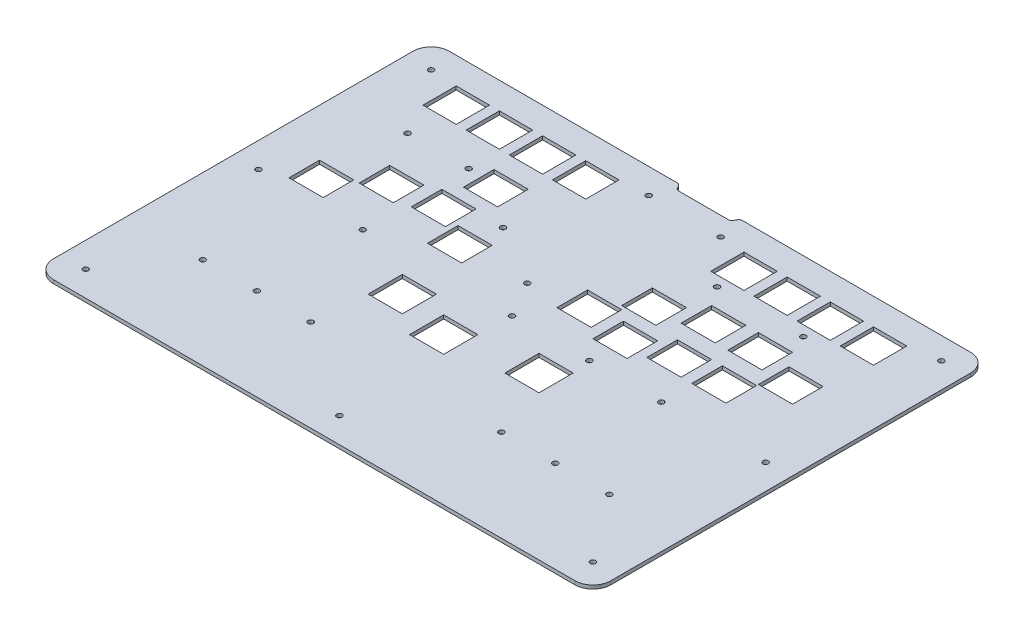
SolidWorks part; units mm, degrees
ref_plane "前视基准面" through (0, 0, 0) normal (0, 0, 1) x (1, 0, 0)
ref_plane "上视基准面" through (0, 0, 0) normal (0, 1, 0) x (1, 0, 0)
ref_plane "右视基准面" through (0, 0, 0) normal (1, 0, 0) x (0, 0, -1)
sketch "草图1" plane through (0, 0, 0) normal (0, 1, 0) x (1, 0, 0)
  line L0 (183.25, -128.5) -> (183.25, -131.5) construction
  line L1 (10, 0) -> (136.8844, 0)
  line L2 (0, -10) -> (0, -210)
  line L3 (10, -220) -> (300, -220)
  line L4 (310, -10) -> (310, -210)
  line L5 (28.75, -14.75) -> (47.25, -14.75)
  line L6 (28.75, -14.75) -> (28.75, -33.25)
  line L7 (28.75, -33.25) -> (47.25, -33.25)
  line L8 (173, -85) -> (173, 0) construction
  line L9 (173, -85) -> (310, -85) construction
  line L10 (190, -66) -> (190, 0) construction
  line L11 (215, -58) -> (215, 0) construction
  line L12 (241, -58) -> (241, 0) construction
  line L13 (247, -84) -> (247, 0) construction
  line L14 (222, -84) -> (222, 0) construction
  line L15 (0, -220) -> (310, 0) construction
  line L16 (241, -58) -> (310, -58) construction
  line L17 (247, -84) -> (310, -84) construction
  line L18 (215, -58) -> (310, -58) construction
  line L19 (222, -84) -> (310, -84) construction
  line L20 (190, -66) -> (310, -66) construction
  line L21 (310, -220) -> (0, 0) construction
  line L22 (141.1791, -3.5) -> (143.5, -3.5)
  line L23 (139.4291, -2.4682) -> (138.6344, -1.0318)
  line L24 (170.5709, -2.4682) -> (171.3656, -1.0318)
  line L25 (173.1156, 0) -> (300, 0)
  line L26 (155, -110) -> (155, -220) construction
  line L27 (47.25, -14.75) -> (47.25, -33.25)
  line L28 (28.75, -14.75) -> (47.25, -33.25) construction
  line L29 (28.75, -33.25) -> (47.25, -14.75) construction
  line L30 (52.75, -14.75) -> (71.25, -14.75)
  line L31 (52.75, -14.75) -> (52.75, -33.25)
  line L32 (52.75, -33.25) -> (71.25, -33.25)
  line L33 (71.25, -14.75) -> (71.25, -33.25)
  line L34 (52.75, -14.75) -> (71.25, -33.25) construction
  line L35 (52.75, -33.25) -> (71.25, -14.75) construction
  line L36 (76.75, -14.75) -> (95.25, -14.75)
  line L37 (76.75, -14.75) -> (76.75, -33.25)
  line L38 (76.75, -33.25) -> (95.25, -33.25)
  line L39 (95.25, -14.75) -> (95.25, -33.25)
  line L40 (76.75, -14.75) -> (95.25, -33.25) construction
  line L41 (76.75, -33.25) -> (95.25, -14.75) construction
  line L42 (100.75, -14.75) -> (119.25, -14.75)
  line L43 (100.75, -14.75) -> (100.75, -33.25)
  line L44 (100.75, -33.25) -> (119.25, -33.25)
  line L45 (119.25, -14.75) -> (119.25, -33.25)
  line L46 (100.75, -14.75) -> (119.25, -33.25) construction
  line L47 (100.75, -33.25) -> (119.25, -14.75) construction
  line L48 (188.75, -14.75) -> (207.25, -14.75)
  line L49 (188.75, -14.75) -> (188.75, -33.25)
  line L50 (188.75, -33.25) -> (207.25, -33.25)
  line L51 (207.25, -14.75) -> (207.25, -33.25)
  line L52 (188.75, -14.75) -> (207.25, -33.25) construction
  line L53 (188.75, -33.25) -> (207.25, -14.75) construction
  line L54 (212.75, -14.75) -> (231.25, -14.75)
  line L55 (212.75, -14.75) -> (212.75, -33.25)
  line L56 (212.75, -33.25) -> (231.25, -33.25)
  line L57 (231.25, -14.75) -> (231.25, -33.25)
  line L58 (212.75, -14.75) -> (231.25, -33.25) construction
  line L59 (212.75, -33.25) -> (231.25, -14.75) construction
  line L60 (236.75, -14.75) -> (255.25, -14.75)
  line L61 (236.75, -14.75) -> (236.75, -33.25)
  line L62 (236.75, -33.25) -> (255.25, -33.25)
  line L63 (255.25, -14.75) -> (255.25, -33.25)
  line L64 (236.75, -14.75) -> (255.25, -33.25) construction
  line L65 (236.75, -33.25) -> (255.25, -14.75) construction
  line L66 (260.75, -14.75) -> (279.25, -14.75)
  line L67 (260.75, -14.75) -> (260.75, -33.25)
  line L68 (260.75, -33.25) -> (279.25, -33.25)
  line L69 (279.25, -14.75) -> (279.25, -33.25)
  line L70 (260.75, -14.75) -> (279.25, -33.25) construction
  line L71 (260.75, -33.25) -> (279.25, -14.75) construction
  line L72 (183, -123) -> (197, -123) construction
  line L73 (183, -123) -> (183, -128.25) construction
  line L74 (183, -137) -> (197, -137) construction
  line L75 (197, -123) -> (197, -128.25) construction
  line L76 (183, -123) -> (197, -137) construction
  line L77 (183, -137) -> (197, -123) construction
  line L78 (183.25, -128.5) -> (183, -128.25) construction
  line L79 (183.25, -131.5) -> (183, -131.75) construction
  line L80 (196.75, -128.5) -> (196.75, -131.5) construction
  line L81 (196.75, -128.5) -> (197, -128.25) construction
  line L82 (196.75, -131.5) -> (197, -131.75) construction
  line L83 (183, -131.75) -> (183, -137) construction
  line L84 (197, -131.75) -> (197, -137) construction
  line L85 (31.25, -22.5) -> (31.25, -25.5) construction
  line L86 (31, -17) -> (45, -17) construction
  line L87 (31, -17) -> (31, -22.25) construction
  line L88 (31, -31) -> (45, -31) construction
  line L89 (45, -17) -> (45, -22.25) construction
  line L90 (31, -17) -> (45, -31) construction
  line L91 (31, -31) -> (45, -17) construction
  line L92 (31.25, -22.5) -> (31, -22.25) construction
  line L93 (31.25, -25.5) -> (31, -25.75) construction
  line L94 (44.75, -22.5) -> (44.75, -25.5) construction
  line L95 (44.75, -22.5) -> (45, -22.25) construction
  line L96 (44.75, -25.5) -> (45, -25.75) construction
  line L97 (31, -25.75) -> (31, -31) construction
  line L98 (45, -25.75) -> (45, -31) construction
  line L99 (55.25, -22.5) -> (55.25, -25.5) construction
  line L100 (55, -17) -> (69, -17) construction
  line L101 (55, -17) -> (55, -22.25) construction
  line L102 (55, -31) -> (69, -31) construction
  line L103 (69, -17) -> (69, -22.25) construction
  line L104 (55, -17) -> (69, -31) construction
  line L105 (55, -31) -> (69, -17) construction
  line L106 (55.25, -22.5) -> (55, -22.25) construction
  line L107 (55.25, -25.5) -> (55, -25.75) construction
  line L108 (68.75, -22.5) -> (68.75, -25.5) construction
  line L109 (68.75, -22.5) -> (69, -22.25) construction
  line L110 (68.75, -25.5) -> (69, -25.75) construction
  line L111 (55, -25.75) -> (55, -31) construction
  line L112 (69, -25.75) -> (69, -31) construction
  line L113 (79.25, -22.5) -> (79.25, -25.5) construction
  line L114 (79, -17) -> (93, -17) construction
  line L115 (79, -17) -> (79, -22.25) construction
  line L116 (79, -31) -> (93, -31) construction
  line L117 (93, -17) -> (93, -22.25) construction
  line L118 (79, -17) -> (93, -31) construction
  line L119 (79, -31) -> (93, -17) construction
  line L120 (79.25, -22.5) -> (79, -22.25) construction
  line L121 (79.25, -25.5) -> (79, -25.75) construction
  line L122 (92.75, -22.5) -> (92.75, -25.5) construction
  line L123 (92.75, -22.5) -> (93, -22.25) construction
  line L124 (92.75, -25.5) -> (93, -25.75) construction
  line L125 (79, -25.75) -> (79, -31) construction
  line L126 (93, -25.75) -> (93, -31) construction
  line L127 (103.25, -22.5) -> (103.25, -25.5) construction
  line L128 (103, -17) -> (117, -17) construction
  line L129 (103, -17) -> (103, -22.25) construction
  line L130 (103, -31) -> (117, -31) construction
  line L131 (117, -17) -> (117, -22.25) construction
  line L132 (103, -17) -> (117, -31) construction
  line L133 (103, -31) -> (117, -17) construction
  line L134 (103.25, -22.5) -> (103, -22.25) construction
  line L135 (103.25, -25.5) -> (103, -25.75) construction
  line L136 (116.75, -22.5) -> (116.75, -25.5) construction
  line L137 (116.75, -22.5) -> (117, -22.25) construction
  line L138 (116.75, -25.5) -> (117, -25.75) construction
  line L139 (103, -25.75) -> (103, -31) construction
  line L140 (117, -25.75) -> (117, -31) construction
  line L141 (191.25, -22.5) -> (191.25, -25.5) construction
  line L142 (191, -17) -> (205, -17) construction
  line L143 (191, -17) -> (191, -22.25) construction
  line L144 (191, -31) -> (205, -31) construction
  line L145 (205, -17) -> (205, -22.25) construction
  line L146 (191, -17) -> (205, -31) construction
  line L147 (191, -31) -> (205, -17) construction
  line L148 (191.25, -22.5) -> (191, -22.25) construction
  line L149 (191.25, -25.5) -> (191, -25.75) construction
  line L150 (204.75, -22.5) -> (204.75, -25.5) construction
  line L151 (204.75, -22.5) -> (205, -22.25) construction
  line L152 (204.75, -25.5) -> (205, -25.75) construction
  line L153 (191, -25.75) -> (191, -31) construction
  line L154 (205, -25.75) -> (205, -31) construction
  line L155 (215.25, -22.5) -> (215.25, -25.5) construction
  line L156 (215, -17) -> (229, -17) construction
  line L157 (215, -17) -> (215, -22.25) construction
  line L158 (215, -31) -> (229, -31) construction
  line L159 (229, -17) -> (229, -22.25) construction
  line L160 (215, -17) -> (229, -31) construction
  line L161 (215, -31) -> (229, -17) construction
  line L162 (215.25, -22.5) -> (215, -22.25) construction
  line L163 (215.25, -25.5) -> (215, -25.75) construction
  line L164 (228.75, -22.5) -> (228.75, -25.5) construction
  line L165 (228.75, -22.5) -> (229, -22.25) construction
  line L166 (228.75, -25.5) -> (229, -25.75) construction
  line L167 (215, -25.75) -> (215, -31) construction
  line L168 (229, -25.75) -> (229, -31) construction
  line L169 (239.25, -22.5) -> (239.25, -25.5) construction
  line L170 (239, -17) -> (253, -17) construction
  line L171 (239, -17) -> (239, -22.25) construction
  line L172 (239, -31) -> (253, -31) construction
  line L173 (253, -17) -> (253, -22.25) construction
  line L174 (239, -17) -> (253, -31) construction
  line L175 (239, -31) -> (253, -17) construction
  line L176 (239.25, -22.5) -> (239, -22.25) construction
  line L177 (239.25, -25.5) -> (239, -25.75) construction
  line L178 (252.75, -22.5) -> (252.75, -25.5) construction
  line L179 (252.75, -22.5) -> (253, -22.25) construction
  line L180 (252.75, -25.5) -> (253, -25.75) construction
  line L181 (239, -25.75) -> (239, -31) construction
  line L182 (253, -25.75) -> (253, -31) construction
  line L183 (263.25, -22.5) -> (263.25, -25.5) construction
  line L184 (263, -17) -> (277, -17) construction
  line L185 (263, -17) -> (263, -22.25) construction
  line L186 (263, -31) -> (277, -31) construction
  line L187 (277, -17) -> (277, -22.25) construction
  line L188 (263, -17) -> (277, -31) construction
  line L189 (263, -31) -> (277, -17) construction
  line L190 (263.25, -22.5) -> (263, -22.25) construction
  line L191 (263.25, -25.5) -> (263, -25.75) construction
  line L192 (276.75, -22.5) -> (276.75, -25.5) construction
  line L193 (276.75, -22.5) -> (277, -22.25) construction
  line L194 (276.75, -25.5) -> (277, -25.75) construction
  line L195 (263, -25.75) -> (263, -31) construction
  line L196 (277, -25.75) -> (277, -31) construction
  line L197 (259.25, -64.5) -> (259.25, -67.5) construction
  line L198 (259, -59) -> (273, -59) construction
  line L199 (259, -59) -> (259, -64.25) construction
  line L200 (259, -73) -> (273, -73) construction
  line L201 (273, -59) -> (273, -64.25) construction
  line L202 (259, -59) -> (273, -73) construction
  line L203 (259, -73) -> (273, -59) construction
  line L204 (259.25, -64.5) -> (259, -64.25) construction
  line L205 (259.25, -67.5) -> (259, -67.75) construction
  line L206 (272.75, -64.5) -> (272.75, -67.5) construction
  line L207 (272.75, -64.5) -> (273, -64.25) construction
  line L208 (272.75, -67.5) -> (273, -67.75) construction
  line L209 (259, -67.75) -> (259, -73) construction
  line L210 (273, -67.75) -> (273, -73) construction
  line L211 (240.25, -82.5) -> (240.25, -85.5) construction
  line L212 (240, -77) -> (254, -77) construction
  line L213 (240, -77) -> (240, -82.25) construction
  line L214 (240, -91) -> (254, -91) construction
  line L215 (254, -77) -> (254, -82.25) construction
  line L216 (240, -77) -> (254, -91) construction
  line L217 (240, -91) -> (254, -77) construction
  line L218 (240.25, -82.5) -> (240, -82.25) construction
  line L219 (240.25, -85.5) -> (240, -85.75) construction
  line L220 (253.75, -82.5) -> (253.75, -85.5) construction
  line L221 (253.75, -82.5) -> (254, -82.25) construction
  line L222 (253.75, -85.5) -> (254, -85.75) construction
  line L223 (240, -85.75) -> (240, -91) construction
  line L224 (254, -85.75) -> (254, -91) construction
  line L225 (234.25, -56.5) -> (234.25, -59.5) construction
  line L226 (234, -51) -> (248, -51) construction
  line L227 (234, -51) -> (234, -56.25) construction
  line L228 (234, -65) -> (248, -65) construction
  line L229 (248, -51) -> (248, -56.25) construction
  line L230 (234, -51) -> (248, -65) construction
  line L231 (234, -65) -> (248, -51) construction
  line L232 (234.25, -56.5) -> (234, -56.25) construction
  line L233 (234.25, -59.5) -> (234, -59.75) construction
  line L234 (247.75, -56.5) -> (247.75, -59.5) construction
  line L235 (247.75, -56.5) -> (248, -56.25) construction
  line L236 (247.75, -59.5) -> (248, -59.75) construction
  line L237 (234, -59.75) -> (234, -65) construction
  line L238 (248, -59.75) -> (248, -65) construction
  line L239 (215.25, -82.5) -> (215.25, -85.5) construction
  line L240 (215, -77) -> (229, -77) construction
  line L241 (215, -77) -> (215, -82.25) construction
  line L242 (215, -91) -> (229, -91) construction
  line L243 (229, -77) -> (229, -82.25) construction
  line L244 (215, -77) -> (229, -91) construction
  line L245 (215, -91) -> (229, -77) construction
  line L246 (215.25, -82.5) -> (215, -82.25) construction
  line L247 (215.25, -85.5) -> (215, -85.75) construction
  line L248 (228.75, -82.5) -> (228.75, -85.5) construction
  line L249 (228.75, -82.5) -> (229, -82.25) construction
  line L250 (228.75, -85.5) -> (229, -85.75) construction
  line L251 (215, -85.75) -> (215, -91) construction
  line L252 (229, -85.75) -> (229, -91) construction
  line L253 (29.25, -95.5) -> (29.25, -98.5) construction
  line L254 (29, -90) -> (43, -90) construction
  line L255 (29, -90) -> (29, -95.25) construction
  line L256 (29, -104) -> (43, -104) construction
  line L257 (43, -90) -> (43, -95.25) construction
  line L258 (29, -90) -> (43, -104) construction
  line L259 (29, -104) -> (43, -90) construction
  line L260 (29.25, -95.5) -> (29, -95.25) construction
  line L261 (29.25, -98.5) -> (29, -98.75) construction
  line L262 (42.75, -95.5) -> (42.75, -98.5) construction
  line L263 (42.75, -95.5) -> (43, -95.25) construction
  line L264 (42.75, -98.5) -> (43, -98.75) construction
  line L265 (29, -98.75) -> (29, -104) construction
  line L266 (43, -98.75) -> (43, -104) construction
  line L267 (51.25, -78.5) -> (51.25, -81.5) construction
  line L268 (51, -73) -> (65, -73) construction
  line L269 (51, -73) -> (51, -78.25) construction
  line L270 (51, -87) -> (65, -87) construction
  line L271 (65, -73) -> (65, -78.25) construction
  line L272 (51, -73) -> (65, -87) construction
  line L273 (51, -87) -> (65, -73) construction
  line L274 (51.25, -78.5) -> (51, -78.25) construction
  line L275 (51.25, -81.5) -> (51, -81.75) construction
  line L276 (64.75, -78.5) -> (64.75, -81.5) construction
  line L277 (64.75, -78.5) -> (65, -78.25) construction
  line L278 (64.75, -81.5) -> (65, -81.75) construction
  line L279 (51, -81.75) -> (51, -87) construction
  line L280 (65, -81.75) -> (65, -87) construction
  line L281 (77.25, -75.5) -> (77.25, -78.5) construction
  line L282 (77, -70) -> (91, -70) construction
  line L283 (77, -70) -> (77, -75.25) construction
  line L284 (77, -84) -> (91, -84) construction
  line L285 (91, -70) -> (91, -75.25) construction
  line L286 (77, -70) -> (91, -84) construction
  line L287 (77, -84) -> (91, -70) construction
  line L288 (77.25, -75.5) -> (77, -75.25) construction
  line L289 (77.25, -78.5) -> (77, -78.75) construction
  line L290 (90.75, -75.5) -> (90.75, -78.5) construction
  line L291 (90.75, -75.5) -> (91, -75.25) construction
  line L292 (90.75, -78.5) -> (91, -78.75) construction
  line L293 (77, -78.75) -> (77, -84) construction
  line L294 (91, -78.75) -> (91, -84) construction
  line L295 (82.25, -51.5) -> (82.25, -54.5) construction
  line L296 (82, -46) -> (96, -46) construction
  line L297 (82, -46) -> (82, -51.25) construction
  line L298 (82, -60) -> (96, -60) construction
  line L299 (96, -46) -> (96, -51.25) construction
  line L300 (82, -46) -> (96, -60) construction
  line L301 (82, -60) -> (96, -46) construction
  line L302 (82.25, -51.5) -> (82, -51.25) construction
  line L303 (82.25, -54.5) -> (82, -54.75) construction
  line L304 (95.75, -51.5) -> (95.75, -54.5) construction
  line L305 (95.75, -51.5) -> (96, -51.25) construction
  line L306 (95.75, -54.5) -> (96, -54.75) construction
  line L307 (82, -54.75) -> (82, -60) construction
  line L308 (96, -54.75) -> (96, -60) construction
  line L309 (99.25, -88.5) -> (99.25, -91.5) construction
  line L310 (99, -83) -> (113, -83) construction
  line L311 (99, -83) -> (99, -88.25) construction
  line L312 (99, -97) -> (113, -97) construction
  line L313 (113, -83) -> (113, -88.25) construction
  line L314 (99, -83) -> (113, -97) construction
  line L315 (99, -97) -> (113, -83) construction
  line L316 (99.25, -88.5) -> (99, -88.25) construction
  line L317 (99.25, -91.5) -> (99, -91.75) construction
  line L318 (112.75, -88.5) -> (112.75, -91.5) construction
  line L319 (112.75, -88.5) -> (113, -88.25) construction
  line L320 (112.75, -91.5) -> (113, -91.75) construction
  line L321 (99, -91.75) -> (99, -97) construction
  line L322 (113, -91.75) -> (113, -97) construction
  line L323 (208.25, -56.5) -> (208.25, -59.5) construction
  line L324 (208, -51) -> (222, -51) construction
  line L325 (208, -51) -> (208, -56.25) construction
  line L326 (208, -65) -> (222, -65) construction
  line L327 (222, -51) -> (222, -56.25) construction
  line L328 (208, -51) -> (222, -65) construction
  line L329 (208, -65) -> (222, -51) construction
  line L330 (208.25, -56.5) -> (208, -56.25) construction
  line L331 (208.25, -59.5) -> (208, -59.75) construction
  line L332 (221.75, -56.5) -> (221.75, -59.5) construction
  line L333 (221.75, -56.5) -> (222, -56.25) construction
  line L334 (221.75, -59.5) -> (222, -59.75) construction
  line L335 (208, -59.75) -> (208, -65) construction
  line L336 (222, -59.75) -> (222, -65) construction
  line L337 (183.25, -64.5) -> (183.25, -67.5) construction
  line L338 (183, -59) -> (197, -59) construction
  line L339 (183, -59) -> (183, -64.25) construction
  line L340 (183, -73) -> (197, -73) construction
  line L341 (197, -59) -> (197, -64.25) construction
  line L342 (183, -59) -> (197, -73) construction
  line L343 (183, -73) -> (197, -59) construction
  line L344 (183.25, -64.5) -> (183, -64.25) construction
  line L345 (183.25, -67.5) -> (183, -67.75) construction
  line L346 (196.75, -64.5) -> (196.75, -67.5) construction
  line L347 (196.75, -64.5) -> (197, -64.25) construction
  line L348 (196.75, -67.5) -> (197, -67.75) construction
  line L349 (183, -67.75) -> (183, -73) construction
  line L350 (197, -67.75) -> (197, -73) construction
  line L351 (191.25, -88.5) -> (191.25, -91.5) construction
  line L352 (191, -83) -> (205, -83) construction
  line L353 (191, -83) -> (191, -88.25) construction
  line L354 (191, -97) -> (205, -97) construction
  line L355 (205, -83) -> (205, -88.25) construction
  line L356 (191, -83) -> (205, -97) construction
  line L357 (191, -97) -> (205, -83) construction
  line L358 (191.25, -88.5) -> (191, -88.25) construction
  line L359 (191.25, -91.5) -> (191, -91.75) construction
  line L360 (204.75, -88.5) -> (204.75, -91.5) construction
  line L361 (204.75, -88.5) -> (205, -88.25) construction
  line L362 (204.75, -91.5) -> (205, -91.75) construction
  line L363 (191, -91.75) -> (191, -97) construction
  line L364 (205, -91.75) -> (205, -97) construction
  line L365 (166.25, -83.5) -> (166.25, -86.5) construction
  line L366 (166, -78) -> (180, -78) construction
  line L367 (166, -78) -> (166, -83.25) construction
  line L368 (166, -92) -> (180, -92) construction
  line L369 (180, -78) -> (180, -83.25) construction
  line L370 (166, -78) -> (180, -92) construction
  line L371 (166, -92) -> (180, -78) construction
  line L372 (166.25, -83.5) -> (166, -83.25) construction
  line L373 (166.25, -86.5) -> (166, -86.75) construction
  line L374 (179.75, -83.5) -> (179.75, -86.5) construction
  line L375 (179.75, -83.5) -> (180, -83.25) construction
  line L376 (179.75, -86.5) -> (180, -86.75) construction
  line L377 (166, -86.75) -> (166, -92) construction
  line L378 (180, -86.75) -> (180, -92) construction
  line L379 (107.25, -128.5) -> (107.25, -131.5) construction
  line L380 (107, -123) -> (121, -123) construction
  line L381 (107, -123) -> (107, -128.25) construction
  line L382 (107, -137) -> (121, -137) construction
  line L383 (121, -123) -> (121, -128.25) construction
  line L384 (107, -123) -> (121, -137) construction
  line L385 (107, -137) -> (121, -123) construction
  line L386 (107.25, -128.5) -> (107, -128.25) construction
  line L387 (107.25, -131.5) -> (107, -131.75) construction
  line L388 (120.75, -128.5) -> (120.75, -131.5) construction
  line L389 (120.75, -128.5) -> (121, -128.25) construction
  line L390 (120.75, -131.5) -> (121, -131.75) construction
  line L391 (107, -131.75) -> (107, -137) construction
  line L392 (121, -131.75) -> (121, -137) construction
  line L393 (138.25, -136.5) -> (138.25, -139.5) construction
  line L394 (138, -131) -> (152, -131) construction
  line L395 (138, -131) -> (138, -136.25) construction
  line L396 (138, -145) -> (152, -145) construction
  line L397 (152, -131) -> (152, -136.25) construction
  line L398 (138, -131) -> (152, -145) construction
  line L399 (138, -145) -> (152, -131) construction
  line L400 (138.25, -136.5) -> (138, -136.25) construction
  line L401 (138.25, -139.5) -> (138, -139.75) construction
  line L402 (151.75, -136.5) -> (151.75, -139.5) construction
  line L403 (151.75, -136.5) -> (152, -136.25) construction
  line L404 (151.75, -139.5) -> (152, -139.75) construction
  line L405 (138, -139.75) -> (138, -145) construction
  line L406 (152, -139.75) -> (152, -145) construction
  line L407 (166.5, -3.5) -> (168.8209, -3.5)
  line L409 (143.5, -3.5) -> (143.5, -55.5) construction
  line L410 (143.5, -55.5) -> (166.5, -55.5) construction
  line L411 (166.5, -3.5) -> (166.5, -55.5) construction
  line L412 (143.5, -3.5) -> (166.5, -55.5) construction
  line L413 (143.5, -55.5) -> (166.5, -3.5) construction
  line L414 (143.5, -3.5) -> (166.5, -3.5)
  line L415 (79.5, -44.5) -> (98.5, -44.5)
  line L422 (79.5, -44.5) -> (79.5, -61.5)
  line L423 (79.5, -61.5) -> (98.5, -61.5)
  line L424 (98.5, -44.5) -> (98.5, -61.5)
  line L425 (79.5, -44.5) -> (98.5, -61.5) construction
  line L426 (79.5, -61.5) -> (98.5, -44.5) construction
  line L427 (74.5, -68.5) -> (93.5, -68.5)
  line L428 (74.5, -68.5) -> (74.5, -85.5)
  line L429 (74.5, -85.5) -> (93.5, -85.5)
  line L430 (93.5, -68.5) -> (93.5, -85.5)
  line L431 (74.5, -68.5) -> (93.5, -85.5) construction
  line L432 (74.5, -85.5) -> (93.5, -68.5) construction
  line L433 (96.5, -81.5) -> (115.5, -81.5)
  line L434 (96.5, -81.5) -> (96.5, -98.5)
  line L435 (96.5, -98.5) -> (115.5, -98.5)
  line L436 (115.5, -81.5) -> (115.5, -98.5)
  line L437 (96.5, -81.5) -> (115.5, -98.5) construction
  line L438 (96.5, -98.5) -> (115.5, -81.5) construction
  line L439 (48.5, -71.5) -> (67.5, -71.5)
  line L440 (48.5, -71.5) -> (48.5, -88.5)
  line L441 (48.5, -88.5) -> (67.5, -88.5)
  line L442 (67.5, -71.5) -> (67.5, -88.5)
  line L443 (48.5, -71.5) -> (67.5, -88.5) construction
  line L444 (48.5, -88.5) -> (67.5, -71.5) construction
  line L445 (26.5, -88.5) -> (45.5, -88.5)
  line L446 (26.5, -88.5) -> (26.5, -105.5)
  line L447 (26.5, -105.5) -> (45.5, -105.5)
  line L448 (45.5, -88.5) -> (45.5, -105.5)
  line L449 (26.5, -88.5) -> (45.5, -105.5) construction
  line L450 (26.5, -105.5) -> (45.5, -88.5) construction
  line L451 (104.5, -120.5) -> (123.5, -120.5)
  line L452 (104.5, -120.5) -> (104.5, -139.5)
  line L453 (104.5, -139.5) -> (123.5, -139.5)
  line L454 (123.5, -120.5) -> (123.5, -139.5)
  line L455 (104.5, -120.5) -> (123.5, -139.5) construction
  line L456 (104.5, -139.5) -> (123.5, -120.5) construction
  line L457 (135.5, -128.5) -> (154.5, -128.5)
  line L458 (135.5, -128.5) -> (135.5, -147.5)
  line L459 (135.5, -147.5) -> (154.5, -147.5)
  line L460 (154.5, -128.5) -> (154.5, -147.5)
  line L461 (135.5, -128.5) -> (154.5, -147.5) construction
  line L462 (135.5, -147.5) -> (154.5, -128.5) construction
  line L463 (180.5, -120.5) -> (199.5, -120.5)
  line L464 (180.5, -120.5) -> (180.5, -139.5)
  line L465 (180.5, -139.5) -> (199.5, -139.5)
  line L466 (199.5, -120.5) -> (199.5, -139.5)
  line L467 (180.5, -120.5) -> (199.5, -139.5) construction
  line L468 (180.5, -139.5) -> (199.5, -120.5) construction
  line L469 (163.5, -76.5) -> (182.5, -76.5)
  line L470 (163.5, -76.5) -> (163.5, -93.5)
  line L471 (163.5, -93.5) -> (182.5, -93.5)
  line L472 (182.5, -76.5) -> (182.5, -93.5)
  line L473 (163.5, -76.5) -> (182.5, -93.5) construction
  line L474 (163.5, -93.5) -> (182.5, -76.5) construction
  line L475 (180.5, -57.5) -> (199.5, -57.5)
  line L476 (180.5, -57.5) -> (180.5, -74.5)
  line L477 (180.5, -74.5) -> (199.5, -74.5)
  line L478 (199.5, -57.5) -> (199.5, -74.5)
  line L479 (180.5, -57.5) -> (199.5, -74.5) construction
  line L480 (180.5, -74.5) -> (199.5, -57.5) construction
  line L481 (188.5, -81.5) -> (207.5, -81.5)
  line L482 (188.5, -81.5) -> (188.5, -98.5)
  line L483 (188.5, -98.5) -> (207.5, -98.5)
  line L484 (207.5, -81.5) -> (207.5, -98.5)
  line L485 (188.5, -81.5) -> (207.5, -98.5) construction
  line L486 (188.5, -98.5) -> (207.5, -81.5) construction
  line L487 (205.5, -49.5) -> (224.5, -49.5)
  line L488 (205.5, -49.5) -> (205.5, -66.5)
  line L489 (205.5, -66.5) -> (224.5, -66.5)
  line L490 (224.5, -49.5) -> (224.5, -66.5)
  line L491 (205.5, -49.5) -> (224.5, -66.5) construction
  line L492 (205.5, -66.5) -> (224.5, -49.5) construction
  line L493 (212.5, -75.5) -> (231.5, -75.5)
  line L494 (212.5, -75.5) -> (212.5, -92.5)
  line L495 (212.5, -92.5) -> (231.5, -92.5)
  line L496 (231.5, -75.5) -> (231.5, -92.5)
  line L497 (212.5, -75.5) -> (231.5, -92.5) construction
  line L498 (212.5, -92.5) -> (231.5, -75.5) construction
  line L499 (231.5, -49.5) -> (250.5, -49.5)
  line L500 (231.5, -49.5) -> (231.5, -66.5)
  line L501 (231.5, -66.5) -> (250.5, -66.5)
  line L502 (250.5, -49.5) -> (250.5, -66.5)
  line L503 (231.5, -49.5) -> (250.5, -66.5) construction
  line L504 (231.5, -66.5) -> (250.5, -49.5) construction
  line L505 (237.5, -75.5) -> (256.5, -75.5)
  line L506 (237.5, -75.5) -> (237.5, -92.5)
  line L507 (237.5, -92.5) -> (256.5, -92.5)
  line L508 (256.5, -75.5) -> (256.5, -92.5)
  line L509 (237.5, -75.5) -> (256.5, -92.5) construction
  line L510 (237.5, -92.5) -> (256.5, -75.5) construction
  line L511 (256.5, -57.5) -> (275.5, -57.5)
  line L512 (256.5, -57.5) -> (256.5, -74.5)
  line L513 (256.5, -74.5) -> (275.5, -74.5)
  line L514 (275.5, -57.5) -> (275.5, -74.5)
  line L515 (256.5, -57.5) -> (275.5, -74.5) construction
  line L516 (256.5, -74.5) -> (275.5, -57.5) construction
  arc A0 (10, 0) -> (0, -10) centre (10, -10) ccw
  arc A1 (0, -210) -> (10, -220) centre (10, -210) ccw
  arc A2 (300, -220) -> (310, -210) centre (300, -210) ccw
  arc A3 (300, 0) -> (310, -10) centre (300, -10) cw
  circle A8 centre (173, -85) radius 11 construction
  circle A9 centre (190, -66) radius 11 construction
  circle A11 centre (215, -58) radius 11 construction
  circle A12 centre (222, -84) radius 11 construction
  circle A13 centre (247, -84) radius 11 construction
  circle A14 centre (241, -58) radius 11 construction
  circle A15 centre (14, -14) radius 1.5
  circle A16 centre (14, -206) radius 1.5
  circle A17 centre (296, -206) radius 1.5
  circle A18 centre (296, -12.2857) radius 1.5
  arc A19 (173.1156, 0) -> (171.3656, -1.0318) centre (173.1156, -2) ccw
  arc A20 (170.5709, -2.4682) -> (168.8209, -3.5) centre (168.8209, -1.5) cw
  arc A21 (141.1791, -3.5) -> (139.4291, -2.4682) centre (141.1791, -1.5) cw
  arc A22 (136.8844, 0) -> (138.6344, -1.0318) centre (136.8844, -2) cw
  circle A24 centre (198, -90) radius 11 construction
  circle A25 centre (114, -130) radius 13.5 construction
  circle A26 centre (190, -130) radius 13.5 construction
  circle A27 centre (155, -206) radius 1.5
  circle A28 centre (175, -14) radius 1.5
  circle A29 centre (145, -138) radius 11 construction
  circle A30 centre (106, -90) radius 11 construction
  circle A31 centre (84, -77) radius 11 construction
  circle A32 centre (58, -80) radius 11 construction
  circle A33 centre (36, -97) radius 11 construction
  circle A34 centre (89, -53) radius 11 construction
  circle A35 centre (266, -66) radius 11 construction
  circle A36 centre (110, -24) radius 4.5 construction
  circle A37 centre (86, -24) radius 4.5 construction
  circle A38 centre (62, -24) radius 4.5 construction
  circle A39 centre (38, -24) radius 4.5 construction
  circle A40 centre (198, -24) radius 4.5 construction
  circle A41 centre (222, -24) radius 4.5 construction
  circle A42 centre (246, -24) radius 4.5 construction
  circle A43 centre (270, -24) radius 4.5 construction
  circle A48 centre (135, -14) radius 1.5
  circle A51 centre (296, -110) radius 1.5
  circle A52 centre (14, -110) radius 1.5
  circle A53 centre (155, -110) radius 1.5
  circle A54 centre (72, -110) radius 1.5
  circle A55 centre (72, -168.9032) radius 1.5
  circle A56 centre (72, -51.0968) radius 1.5
  circle A57 centre (42, -168.9032) radius 1.5
  circle A58 centre (102, -168.9032) radius 1.5
  circle A59 centre (238, -110) radius 1.5
  circle A60 centre (238, -168.9032) radius 1.5
  circle A61 centre (268, -168.9032) radius 1.5
  circle A62 centre (208, -168.9032) radius 1.5
  circle A63 centre (246, -39) radius 1.5
  circle A64 centre (198, -39) radius 1.5
  circle A65 centre (110, -70) radius 1.5
  circle A66 centre (38, -51.0968) radius 1.5
  circle A67 centre (198, -110) radius 1.5
  circle A68 centre (143.5, -90) radius 1.5
  point P8 (0, 0)
  point P12 (0, -220)
  point P15 (310, -220)
  point P18 (310, 0)
  point P70 (171.9365, 0)
  point P73 (170, -3.5)
  point P76 (140, -3.5)
  point P79 (138.0635, 0)
  point P147 (190, -130)
  point P152 (155, -29.5)
  point P155 (183.25, -130)
  point P160 (196.75, -130)
  point P163 (38, -24)
  point P170 (31.25, -24)
  point P175 (44.75, -24)
  point P180 (62, -24)
  point P187 (55.25, -24)
  point P192 (68.75, -24)
  point P196 (86, -24)
  point P203 (79.25, -24)
  point P208 (92.75, -24)
  point P213 (110, -24)
  point P220 (103.25, -24)
  point P225 (116.75, -24)
  point P229 (198, -24)
  point P236 (191.25, -24)
  point P241 (204.75, -24)
  point P245 (222, -24)
  point P252 (215.25, -24)
  point P257 (228.75, -24)
  point P261 (246, -24)
  point P268 (239.25, -24)
  point P273 (252.75, -24)
  point P276 (89, -53)
  point P277 (270, -24)
  point P284 (263.25, -24)
  point P289 (276.75, -24)
  point P293 (266, -66)
  point P300 (259.25, -66)
  point P305 (272.75, -66)
  point P310 (247, -84)
  point P317 (240.25, -84)
  point P322 (253.75, -84)
  point P326 (241, -58)
  point P333 (234.25, -58)
  point P338 (247.75, -58)
  point P342 (222, -84)
  point P349 (215.25, -84)
  point P354 (228.75, -84)
  point P358 (36, -97)
  point P365 (29.25, -97)
  point P370 (42.75, -97)
  point P374 (58, -80)
  point P381 (51.25, -80)
  point P386 (64.75, -80)
  point P390 (84, -77)
  point P397 (77.25, -77)
  point P402 (90.75, -77)
  point P407 (89, -53)
  point P414 (82.25, -53)
  point P419 (95.75, -53)
  point P423 (106, -90)
  point P430 (99.25, -90)
  point P435 (112.75, -90)
  point P439 (215, -58)
  point P446 (208.25, -58)
  point P451 (221.75, -58)
  point P455 (190, -66)
  point P462 (183.25, -66)
  point P467 (196.75, -66)
  point P471 (198, -90)
  point P478 (191.25, -90)
  point P483 (204.75, -90)
  point P486 (84, -77)
  point P492 (173, -85)
  point P499 (166.25, -85)
  point P504 (179.75, -85)
  point P508 (114, -130)
  point P515 (107.25, -130)
  point P520 (120.75, -130)
  point P524 (145, -138)
  point P531 (138.25, -138)
  point P536 (151.75, -138)
  point P541 (106, -90)
  point P551 (58, -80)
  point P563 (36, -97)
  point P573 (114, -130)
  point P582 (145, -138)
  point P590 (190, -130)
  point P596 (173, -85)
  point P602 (190, -66)
  point P608 (198, -90)
  point P614 (215, -58)
  point P620 (222, -84)
  point P626 (241, -58)
  point P632 (247, -84)
  point P638 (266, -66)
  dimension "D3" = 10
  dimension "D7" = 90
  dimension "D10" = 22
  dimension "D15" = 53
  dimension "D16" = 22
  dimension "D19" = 22
  dimension "D20" = 22
  dimension "D21" = 22
  dimension "D22" = 84
  dimension "D23" = 22
  dimension "D24" = 22
  dimension "D32" = 22
  dimension "D34" = 3
  dimension "D37" = 3
  dimension "D40" = 3
  dimension "D43" = 3
  dimension "D47" = 3.5
  dimension "D50" = 140
  dimension "D51" = 2
  dimension "D52" = 90
  dimension "D54" = 27
  dimension "D56" = 27
  dimension "D59" = 3
  dimension "D61" = 14
  dimension "D62" = 3
  dimension "D64" = 22
  dimension "D8" = 22
  dimension "D9" = 22
  dimension "D11" = 22
  dimension "D12" = 22
  dimension "D13" = 22
  dimension "D76" = 9
  dimension "D84" = 9
  dimension "D86" = 3
  dimension "D89" = 18.5
  dimension "D92" = 18.5
  dimension "D95" = 18.5
  dimension "D98" = 3
  dimension "D101" = 18.5
  dimension "D103" = 18.5
  dimension "D87" = 3
  dimension "D301" = 3
  dimension "D302" = 3
  dimension "D304" = 3
  dimension "D305" = 3
  dimension "D306" = 3
  dimension "D308" = 3
  dimension "D310" = 3
  dimension "D312" = 3
  dimension "D313" = 3
  dimension "D314" = 3
  dimension "D317" = 3
  dimension "D319" = 3
  dimension "D321" = 3
  dimension "D323" = 3
  dimension "D324" = 3
  dimension "D325" = 3
  dimension "D1" = 220
  dimension "D2" = 310
  dimension "D14" = 89
  dimension "D17" = 85
  dimension "D18" = 137
  dimension "D25" = 66
  dimension "D26" = 120
  dimension "D27" = 36
  dimension "D28" = 58
  dimension "D29" = 95
  dimension "D30" = 88
  dimension "D31" = 69
  dimension "D33" = 63
  dimension "D35" = 14
  dimension "D36" = 14
  dimension "D38" = 14
  dimension "D39" = 14
  dimension "D41" = 14
  dimension "D42" = 14
  dimension "D44" = 14
  dimension "D45" = 12.2857
  dimension "D46" = 4
  dimension "D48" = 30
  dimension "D49" = 4
  dimension "D53" = 112
  dimension "D55" = 114
  dimension "D57" = 90
  dimension "D58" = 120
  dimension "D60" = 14
  dimension "D63" = 135
  dimension "D65" = 82
  dimension "D66" = 145
  dimension "D67" = 97
  dimension "D68" = 80
  dimension "D69" = 58
  dimension "D70" = 84
  dimension "D71" = 77
  dimension "D72" = 90
  dimension "D73" = 106
  dimension "D74" = 44
  dimension "D75" = 66
  dimension "D78" = 24
  dimension "D79" = 110
  dimension "D80" = 24
  dimension "D82" = 24
  dimension "D83" = 24
  dimension "D85" = 40
  dimension "D88" = 18.5
  dimension "D90" = 18.5
  dimension "D91" = 18.5
  dimension "D93" = 18.5
  dimension "D94" = 18.5
  dimension "D96" = 18.5
  dimension "D97" = 18.5
  dimension "D99" = 14
  dimension "D100" = 135
  dimension "D102" = 18.5
  dimension "D104" = 18.5
  dimension "D105" = 18.5
  dimension "D106" = 18.5
  dimension "D107" = 14
  dimension "D108" = 14
  dimension "D109" = 0.25
  dimension "D110" = 3
  dimension "D111" = 135
  dimension "D112" = 3
  dimension "D113" = 0.25
  dimension "D114" = 135
  dimension "D115" = 14
  dimension "D116" = 14
  dimension "D117" = 0.25
  dimension "D118" = 3
  dimension "D119" = 135
  dimension "D120" = 3
  dimension "D121" = 0.25
  dimension "D122" = 135
  dimension "D123" = 14
  dimension "D124" = 14
  dimension "D125" = 0.25
  dimension "D126" = 3
  dimension "D127" = 135
  dimension "D128" = 3
  dimension "D129" = 0.25
  dimension "D130" = 135
  dimension "D131" = 14
  dimension "D132" = 14
  dimension "D133" = 0.25
  dimension "D134" = 3
  dimension "D135" = 135
  dimension "D136" = 3
  dimension "D137" = 0.25
  dimension "D138" = 135
  dimension "D139" = 14
  dimension "D140" = 14
  dimension "D141" = 0.25
  dimension "D142" = 3
  dimension "D143" = 135
  dimension "D144" = 3
  dimension "D145" = 0.25
  dimension "D146" = 135
  dimension "D147" = 14
  dimension "D148" = 14
  dimension "D149" = 0.25
  dimension "D150" = 3
  dimension "D151" = 135
  dimension "D152" = 3
  dimension "D153" = 0.25
  dimension "D154" = 135
  dimension "D155" = 14
  dimension "D156" = 14
  dimension "D157" = 0.25
  dimension "D158" = 3
  dimension "D159" = 135
  dimension "D160" = 3
  dimension "D161" = 0.25
  dimension "D162" = 135
  dimension "D163" = 14
  dimension "D164" = 14
  dimension "D165" = 0.25
  dimension "D166" = 3
  dimension "D167" = 135
  dimension "D168" = 3
  dimension "D169" = 0.25
  dimension "D170" = 135
  dimension "D171" = 14
  dimension "D172" = 14
  dimension "D173" = 0.25
  dimension "D174" = 3
  dimension "D175" = 135
  dimension "D176" = 3
  dimension "D177" = 0.25
  dimension "D178" = 135
  dimension "D179" = 14
  dimension "D180" = 14
  dimension "D181" = 0.25
  dimension "D182" = 3
  dimension "D183" = 135
  dimension "D184" = 3
  dimension "D185" = 0.25
  dimension "D186" = 135
  dimension "D187" = 14
  dimension "D188" = 14
  dimension "D189" = 0.25
  dimension "D190" = 3
  dimension "D191" = 135
  dimension "D192" = 3
  dimension "D193" = 0.25
  dimension "D194" = 135
  dimension "D195" = 14
  dimension "D196" = 14
  dimension "D197" = 0.25
  dimension "D198" = 3
  dimension "D199" = 135
  dimension "D200" = 3
  dimension "D201" = 0.25
  dimension "D202" = 135
  dimension "D203" = 14
  dimension "D204" = 14
  dimension "D205" = 0.25
  dimension "D206" = 3
  dimension "D207" = 135
  dimension "D208" = 3
  dimension "D209" = 0.25
  dimension "D210" = 135
  dimension "D211" = 14
  dimension "D212" = 14
  dimension "D213" = 0.25
  dimension "D214" = 3
  dimension "D215" = 135
  dimension "D216" = 3
  dimension "D217" = 0.25
  dimension "D218" = 135
  dimension "D219" = 14
  dimension "D220" = 14
  dimension "D221" = 0.25
  dimension "D222" = 3
  dimension "D223" = 135
  dimension "D224" = 3
  dimension "D225" = 0.25
  dimension "D226" = 135
  dimension "D227" = 14
  dimension "D228" = 14
  dimension "D229" = 0.25
  dimension "D230" = 3
  dimension "D231" = 135
  dimension "D232" = 3
  dimension "D233" = 0.25
  dimension "D234" = 135
  dimension "D235" = 14
  dimension "D236" = 14
  dimension "D237" = 0.25
  dimension "D238" = 3
  dimension "D239" = 135
  dimension "D240" = 3
  dimension "D241" = 0.25
  dimension "D242" = 135
  dimension "D243" = 14
  dimension "D244" = 14
  dimension "D245" = 0.25
  dimension "D246" = 3
  dimension "D247" = 135
  dimension "D248" = 3
  dimension "D249" = 0.25
  dimension "D250" = 135
  dimension "D251" = 14
  dimension "D252" = 14
  dimension "D253" = 0.25
  dimension "D254" = 3
  dimension "D255" = 135
  dimension "D256" = 3
  dimension "D257" = 0.25
  dimension "D258" = 135
  dimension "D259" = 14
  dimension "D260" = 14
  dimension "D261" = 0.25
  dimension "D262" = 3
  dimension "D263" = 135
  dimension "D264" = 3
  dimension "D265" = 0.25
  dimension "D266" = 135
  dimension "D267" = 14
  dimension "D268" = 14
  dimension "D269" = 0.25
  dimension "D270" = 3
  dimension "D271" = 135
  dimension "D272" = 3
  dimension "D273" = 0.25
  dimension "D274" = 135
  dimension "D275" = 14
  dimension "D276" = 14
  dimension "D277" = 0.25
  dimension "D278" = 3
  dimension "D279" = 135
  dimension "D280" = 3
  dimension "D281" = 0.25
  dimension "D282" = 135
  dimension "D283" = 14
  dimension "D284" = 14
  dimension "D285" = 0.25
  dimension "D286" = 3
  dimension "D287" = 135
  dimension "D288" = 3
  dimension "D289" = 0.25
  dimension "D290" = 135
  dimension "D291" = 14
  dimension "D292" = 14
  dimension "D293" = 0.25
  dimension "D294" = 3
  dimension "D295" = 135
  dimension "D296" = 3
  dimension "D297" = 0.25
  dimension "D298" = 135
  dimension "D299" = 23
  dimension "D300" = 52
  dimension "D303" = 72
  dimension "D307" = 30
  dimension "D309" = 30
  dimension "D311" = 72
  dimension "D315" = 30
  dimension "D316" = 30
  dimension "D318" = 15
  dimension "D320" = 15
  dimension "D322" = 46
  dimension "D328" = 19
  dimension "D329" = 17
  dimension "D330" = 19
  dimension "D331" = 17
  dimension "D332" = 19
  dimension "D333" = 17
  dimension "D334" = 19
  dimension "D335" = 17
  dimension "D336" = 19
  dimension "D337" = 17
  dimension "D338" = 19
  dimension "D339" = 19
  dimension "D340" = 19
  dimension "D341" = 19
  dimension "D342" = 19
  dimension "D343" = 19
  dimension "D344" = 19
  dimension "D345" = 17
  dimension "D346" = 19
  dimension "D347" = 17
  dimension "D348" = 19
  dimension "D349" = 17
  dimension "D350" = 19
  dimension "D351" = 17
  dimension "D352" = 19
  dimension "D353" = 17
  dimension "D354" = 19
  dimension "D355" = 17
  dimension "D356" = 19
  dimension "D357" = 17
  dimension "D358" = 19
  dimension "D359" = 17
  dimension "D77" = 4
  dimension "D81" = 4
extrude "凸台-拉伸1" add sketch "草图1" along normal blind 2
